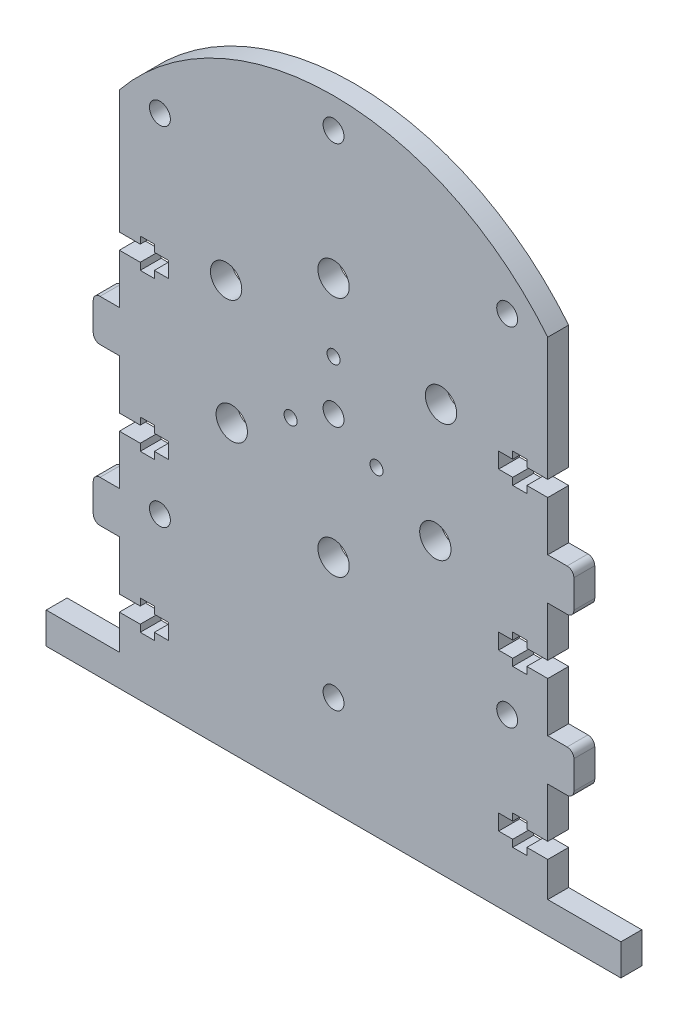
SolidWorks part; units mm, degrees
ref_plane "前视基准面" through (0, 0, 0) normal (0, 0, 1) x (1, 0, 0)
ref_plane "上视基准面" through (0, 0, 0) normal (0, 1, 0) x (1, 0, 0)
ref_plane "右视基准面" through (0, 0, 0) normal (1, 0, 0) x (0, 0, -1)
sketch "草图1" plane through (0, 0, 0) normal (0, 0, 1) x (1, 0, 0)
  line L0 (-14.9625, -1.5035) -> (21.2348, -1.5035) construction
  line L1 (-14.9625, -1.5035) -> (24.3099, -24.1774) construction
  line L2 (-14.9625, -25.2535) -> (-14.9625, -1.5035) construction
  line L3 (26.0375, -61.5035) -> (-55.9625, -61.5035)
  line L4 (26.0375, -61.5035) -> (26.0375, 58.4965) construction
  line L5 (26.0375, 58.4965) -> (-55.9625, 58.4965) construction
  line L7 (26.0375, -61.5035) -> (-55.9625, 58.4965) construction
  line L8 (26.0375, 58.4965) -> (-55.9625, -61.5035) construction
  line L9 (-14.9625, -1.5035) -> (-98.8628, 46.9364) construction
  line L10 (-14.9625, -1.5035) -> (68.9378, 46.9364) construction
  line L11 (-58.2638, 23.4965) -> (-55.9625, 23.4965) construction
  line L12 (-55.9625, 23.4965) -> (-55.9625, 8.1465)
  line L13 (-55.9625, 8.1465) -> (-51.9625, 8.1465)
  line L14 (-51.9625, 8.1465) -> (-51.9625, 9.4965)
  line L15 (-51.9625, 9.4965) -> (-49.2625, 9.4965)
  line L16 (-49.2625, 9.4965) -> (-49.2625, 8.1465)
  line L17 (-49.2625, 8.1465) -> (-46.5625, 8.1465)
  line L18 (-46.5625, 8.1465) -> (-46.5625, 5.1465)
  line L19 (-46.5625, 5.1465) -> (-49.2625, 5.1465)
  line L20 (-49.2625, 5.1465) -> (-49.2625, 3.7965)
  line L21 (-49.2625, 3.7965) -> (-51.9625, 3.7965)
  line L22 (-51.9625, 3.7965) -> (-51.9625, 5.1465)
  line L23 (-51.9625, 5.1465) -> (-55.9625, 5.1465)
  line L24 (-55.9625, -4.3535) -> (-60.9625, -4.3535)
  line L25 (-60.9625, -4.3535) -> (-60.9625, -12.3535)
  line L26 (-60.9625, -12.3535) -> (-55.9625, -12.3535)
  line L27 (-60.9625, -8.3535) -> (-58.1553, -8.3535) construction
  line L28 (-51.9625, -21.8535) -> (-55.9625, -21.8535)
  line L29 (-51.9625, -20.5035) -> (-51.9625, -21.8535)
  line L30 (-49.2625, -20.5035) -> (-51.9625, -20.5035)
  line L31 (-49.2625, -21.8535) -> (-49.2625, -20.5035)
  line L32 (-46.5625, -21.8535) -> (-49.2625, -21.8535)
  line L33 (-46.5625, -24.8535) -> (-46.5625, -21.8535)
  line L34 (-49.2625, -24.8535) -> (-46.5625, -24.8535)
  line L35 (-49.2625, -26.2035) -> (-49.2625, -24.8535)
  line L36 (-51.9625, -26.2035) -> (-49.2625, -26.2035)
  line L37 (-51.9625, -24.8535) -> (-51.9625, -26.2035)
  line L38 (-55.9625, -24.8535) -> (-51.9625, -24.8535)
  line L39 (-55.9625, -21.8535) -> (-55.9625, -12.3535)
  line L40 (-46.5625, -23.3535) -> (-48.2625, -23.3535) construction
  line L41 (-55.9625, -42.3535) -> (-60.9625, -42.3535)
  line L42 (-60.9625, -42.3535) -> (-60.9625, -34.3535)
  line L43 (-60.9625, -34.3535) -> (-55.9625, -34.3535)
  line L44 (-60.9625, -38.3535) -> (-57.1747, -38.3535) construction
  line L45 (-46.5625, -53.3535) -> (-48.2625, -53.3535) construction
  line L46 (-55.9625, 5.1465) -> (-55.9625, -4.3535)
  line L47 (-55.9625, -24.8535) -> (-55.9625, -34.3535)
  line L48 (-55.9625, -51.8535) -> (-51.9625, -51.8535)
  line L49 (-51.9625, -51.8535) -> (-51.9625, -50.5035)
  line L50 (-51.9625, -50.5035) -> (-49.2625, -50.5035)
  line L51 (-49.2625, -50.5035) -> (-49.2625, -51.8535)
  line L52 (-49.2625, -51.8535) -> (-46.5625, -51.8535)
  line L53 (-46.5625, -51.8535) -> (-46.5625, -54.8535)
  line L54 (-46.5625, -54.8535) -> (-49.2625, -54.8535)
  line L55 (-49.2625, -54.8535) -> (-49.2625, -56.2035)
  line L56 (-49.2625, -56.2035) -> (-51.9625, -56.2035)
  line L57 (-51.9625, -56.2035) -> (-51.9625, -54.8535)
  line L58 (-51.9625, -54.8535) -> (-55.9625, -54.8535)
  line L59 (-55.9625, -42.3535) -> (-55.9625, -51.8535)
  line L60 (-55.9625, -54.8535) -> (-55.9625, -61.5035)
  line L61 (16.6375, -53.3535) -> (18.3375, -53.3535) construction
  line L62 (31.0375, -38.3535) -> (27.2497, -38.3535) construction
  line L63 (16.6375, -23.3535) -> (18.3375, -23.3535) construction
  line L64 (31.0375, -8.3535) -> (28.2303, -8.3535) construction
  line L65 (26.0375, -42.3535) -> (26.0375, -51.8535)
  line L66 (22.0375, -54.8535) -> (26.0375, -54.8535)
  line L67 (22.0375, -56.2035) -> (22.0375, -54.8535)
  line L68 (19.3375, -56.2035) -> (22.0375, -56.2035)
  line L69 (19.3375, -54.8535) -> (19.3375, -56.2035)
  line L70 (16.6375, -54.8535) -> (19.3375, -54.8535)
  line L71 (16.6375, -51.8535) -> (16.6375, -54.8535)
  line L72 (19.3375, -51.8535) -> (16.6375, -51.8535)
  line L73 (19.3375, -50.5035) -> (19.3375, -51.8535)
  line L74 (22.0375, -50.5035) -> (19.3375, -50.5035)
  line L75 (22.0375, -51.8535) -> (22.0375, -50.5035)
  line L76 (26.0375, -51.8535) -> (22.0375, -51.8535)
  line L77 (26.0375, -24.8535) -> (26.0375, -34.3535)
  line L78 (26.0375, 5.1465) -> (26.0375, -4.3535)
  line L79 (31.0375, -34.3535) -> (26.0375, -34.3535)
  line L80 (31.0375, -42.3535) -> (31.0375, -34.3535)
  line L81 (26.0375, -42.3535) -> (31.0375, -42.3535)
  line L82 (26.0375, -21.8535) -> (26.0375, -12.3535)
  line L83 (26.0375, -24.8535) -> (22.0375, -24.8535)
  line L84 (22.0375, -24.8535) -> (22.0375, -26.2035)
  line L85 (22.0375, -26.2035) -> (19.3375, -26.2035)
  line L86 (19.3375, -26.2035) -> (19.3375, -24.8535)
  line L87 (19.3375, -24.8535) -> (16.6375, -24.8535)
  line L88 (16.6375, -24.8535) -> (16.6375, -21.8535)
  line L89 (16.6375, -21.8535) -> (19.3375, -21.8535)
  line L90 (19.3375, -21.8535) -> (19.3375, -20.5035)
  line L91 (19.3375, -20.5035) -> (22.0375, -20.5035)
  line L92 (22.0375, -20.5035) -> (22.0375, -21.8535)
  line L93 (22.0375, -21.8535) -> (26.0375, -21.8535)
  line L94 (31.0375, -12.3535) -> (26.0375, -12.3535)
  line L95 (31.0375, -4.3535) -> (31.0375, -12.3535)
  line L96 (26.0375, -4.3535) -> (31.0375, -4.3535)
  line L97 (22.0375, 5.1465) -> (26.0375, 5.1465)
  line L98 (22.0375, 3.7965) -> (22.0375, 5.1465)
  line L99 (19.3375, 3.7965) -> (22.0375, 3.7965)
  line L100 (19.3375, 5.1465) -> (19.3375, 3.7965)
  line L101 (16.6375, 5.1465) -> (19.3375, 5.1465)
  line L102 (16.6375, 8.1465) -> (16.6375, 5.1465)
  line L103 (19.3375, 8.1465) -> (16.6375, 8.1465)
  line L104 (19.3375, 9.4965) -> (19.3375, 8.1465)
  line L105 (22.0375, 9.4965) -> (19.3375, 9.4965)
  line L106 (22.0375, 8.1465) -> (22.0375, 9.4965)
  line L107 (26.0375, 8.1465) -> (22.0375, 8.1465)
  line L108 (26.0375, 23.4965) -> (26.0375, 8.1465)
  line L109 (28.3388, 23.4965) -> (26.0375, 23.4965) construction
  line L110 (26.0375, -54.8535) -> (26.0375, -61.5035)
  line L115 (-55.9625, 23.4965) -> (-55.9625, 31.723)
  line L116 (26.0375, 23.4965) -> (26.0375, 31.723)
  circle A0 centre (-14.9625, -1.5035) radius 23.75 construction
  circle A1 centre (-14.9625, -1.5035) radius 22.5 construction
  circle A2 centre (-14.9625, -25.2535) radius 3
  circle A5 centre (4.5231, -12.7535) radius 3
  circle A8 centre (-14.9625, -1.5035) radius 2
  circle A15 centre (-14.9625, -1.5035) radius 47 construction
  circle A17 centre (-35.5306, 10.3715) radius 3
  circle A18 centre (-34.4481, -12.7535) radius 3
  circle A19 centre (5.6056, 10.3715) radius 3
  circle A20 centre (-14.9625, 20.9965) radius 3
  circle A21 centre (32.0375, -1.5035) radius 2 construction
  circle A22 centre (18.2715, -34.7375) radius 2
  circle A23 centre (-14.9625, -48.5035) radius 2
  circle A24 centre (-48.1965, -34.7375) radius 2
  circle A25 centre (-61.9625, -1.5035) radius 2 construction
  circle A26 centre (-48.1965, 31.7305) radius 2
  circle A27 centre (-14.9625, 45.4965) radius 2
  circle A28 centre (18.2715, 31.7305) radius 2
  circle A31 centre (-14.9625, -1.5035) radius 52.7731 construction
  arc A34 (-55.9625, 31.723) -> (26.0375, 31.723) centre (-14.9625, -1.5035) cw
  circle A35 centre (-14.9625, -1.5035) radius 9.5 construction
  circle A36 centre (-14.9625, 7.9965) radius 1.25
  circle A37 centre (-6.7352, -6.2535) radius 1.25
  circle A38 centre (-23.1897, -6.2535) radius 1.25
  point P41 (-54.9625, -8.3535)
  point P135 (25.0375, -8.3535)
  dimension "D1" = 47.5
  dimension "D2" = 45
  dimension "D3" = 6
  dimension "D5" = 6
  dimension "D18" = 60
  dimension "D19" = 8
  dimension "D20" = 4
  dimension "D21" = 94
  dimension "D22" = 19
  dimension "D23" = 3
  dimension "D4" = 30
  dimension "D6" = 82
  dimension "D8" = 120
  dimension "D9" = 3
  dimension "D10" = 2.7
  dimension "D11" = 5.7
  dimension "D12" = 4
  dimension "D13" = 14
  dimension "D14" = 13.5
  dimension "D15" = 8
  dimension "D16" = 5
  dimension "D17" = 4
  dimension "D7" = 3
extrude "凸台-拉伸2" add sketch "草图1" along normal blind 4
sketch "草图2" plane through (-55.9625, 0, 0) normal (-1, 0, 0) x (0, 0, 1)
  line L0 (2, -54.8535) -> (2, -51.8535)
  line L1 (4, -54.8535) -> (0, -54.8535) construction
  line L2 (4, -51.8535) -> (0, -51.8535) construction
  circle A0 centre (2, -53.3535) radius 1.5
sketch "草图3" plane through (26.0375, 0, 0) normal (1, 0, 0) x (0, 0, -1)
  line L0 (-2, -51.8535) -> (-2, -54.8535)
  line L1 (-4, -51.8535) -> (0, -51.8535) construction
  line L2 (-4, -54.8535) -> (0, -54.8535) construction
  circle A0 centre (-2, -53.3535) radius 1.5
sketch "草图4" plane through (0, 0, 4) normal (0, 0, 1) x (1, 0, 0)
  line L0 (26.0375, -61.5035) -> (26.0375, -54.8535) construction
  line L1 (-69.9625, -61.5035) -> (40.0375, -61.5035)
  line L2 (-69.9625, -61.5035) -> (-69.9625, -67.5035)
  line L3 (-69.9625, -67.5035) -> (40.0375, -67.5035)
  line L4 (40.0375, -61.5035) -> (40.0375, -67.5035)
  line L5 (-55.9625, -54.8535) -> (-55.9625, -61.5035) construction
  line L6 (-55.9625, -61.5035) -> (26.0375, -61.5035) construction
  dimension "D1" = 14
  dimension "D2" = 14
  dimension "D3" = 6
extrude "凸台-拉伸3" add sketch "草图4" against normal blind 4
fillet "圆角1" radius 1.3 8 edges at (-60.9625, -4.3535, 2) (-60.9625, -34.3535, 2) (-60.9625, -12.3535, 2) (-60.9625, -42.3535, 2) (31.0375, -42.3535, 2) (31.0375, -34.3535, 2) (31.0375, -4.3535, 2) (31.0375, -12.3535, 2)
